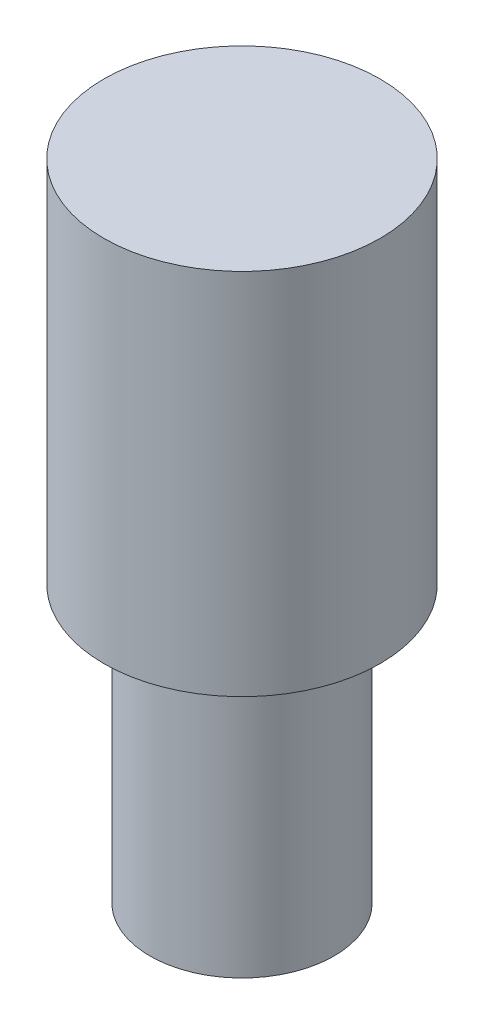
SolidWorks part; units mm, degrees
ref_plane "Front Plane" through (0, 0, 0) normal (0, 0, 1) x (1, 0, 0)
ref_plane "Top Plane" through (0, 0, 0) normal (0, 1, 0) x (1, 0, 0)
ref_plane "Right Plane" through (0, 0, 0) normal (1, 0, 0) x (0, 0, -1)
sketch "Sketch1" plane through (0, 0, 0) normal (0, 0, 1) x (1, 0, 0)
  line L0 (0, 0) -> (0, 7)
  line L1 (0, 7) -> (1.5, 7)
  line L2 (1.5, 7) -> (1.5, 3)
  line L3 (0, 0) -> (1, 0)
  line L4 (1, 0) -> (1, 3)
  line L5 (1, 3) -> (1.5, 3)
  dimension "D1" = 3
  dimension "D2" = 4
  dimension "D3" = 1.5
  dimension "D4" = 1
revolve "Revolve1" add sketch "Sketch1" angle 360 about L0
